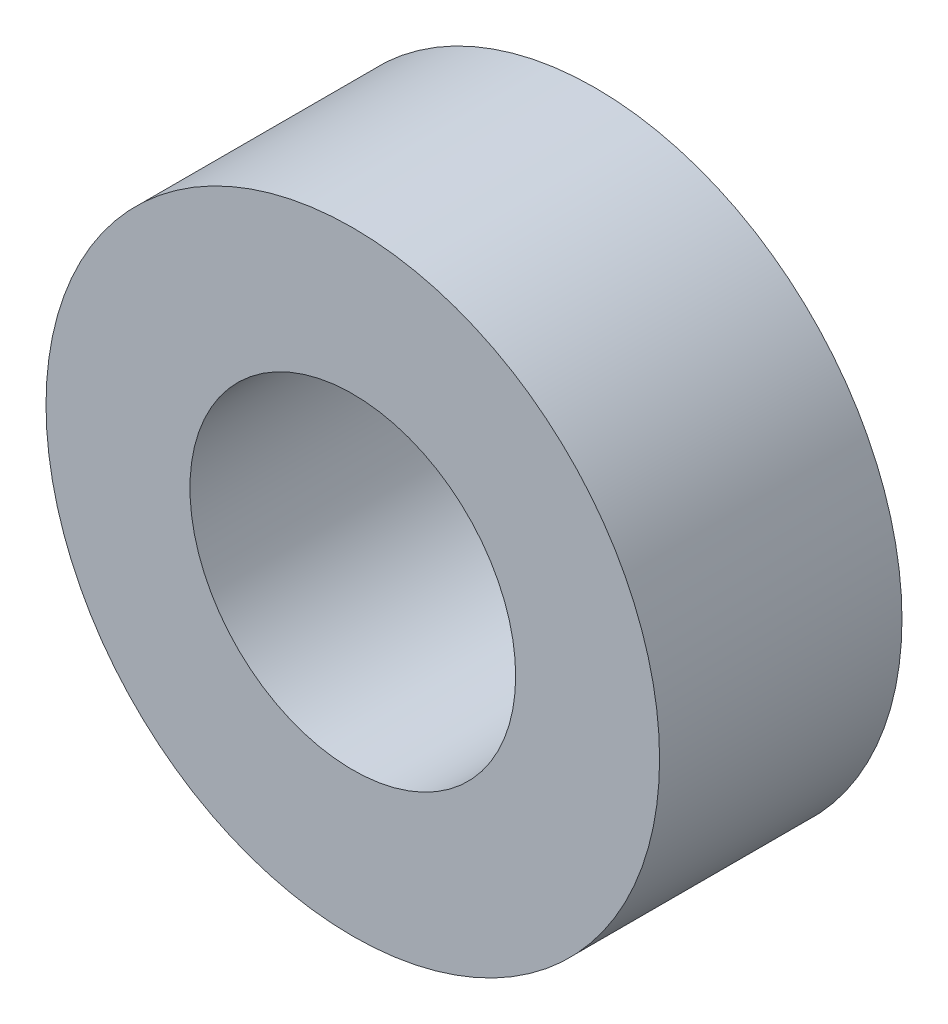
SolidWorks part; units mm, degrees
ref_plane "前视基准面" through (0, 0, 0) normal (0, 0, 1) x (1, 0, 0)
ref_plane "上视基准面" through (0, 0, 0) normal (0, 1, 0) x (1, 0, 0)
ref_plane "右视基准面" through (0, 0, 0) normal (1, 0, 0) x (0, 0, -1)
sketch "草图1" plane through (0, 0, 0) normal (0, 0, 1) x (1, 0, 0)
  circle A0 centre (0, 0) radius 4.05
  dimension "D1" = 8.1
extrude "金属件无牙型包络" add sketch "草图1" along normal blind 3.2
sketch "草图2" plane through (0, 0, 0) normal (0, 0, 1) x (1, 0, 0)
  circle A0 centre (0, 0) radius 2.15
  dimension "D1" = 4.3
extrude "内孔_装配间隙" cut sketch "草图2" along normal blind 3.2
